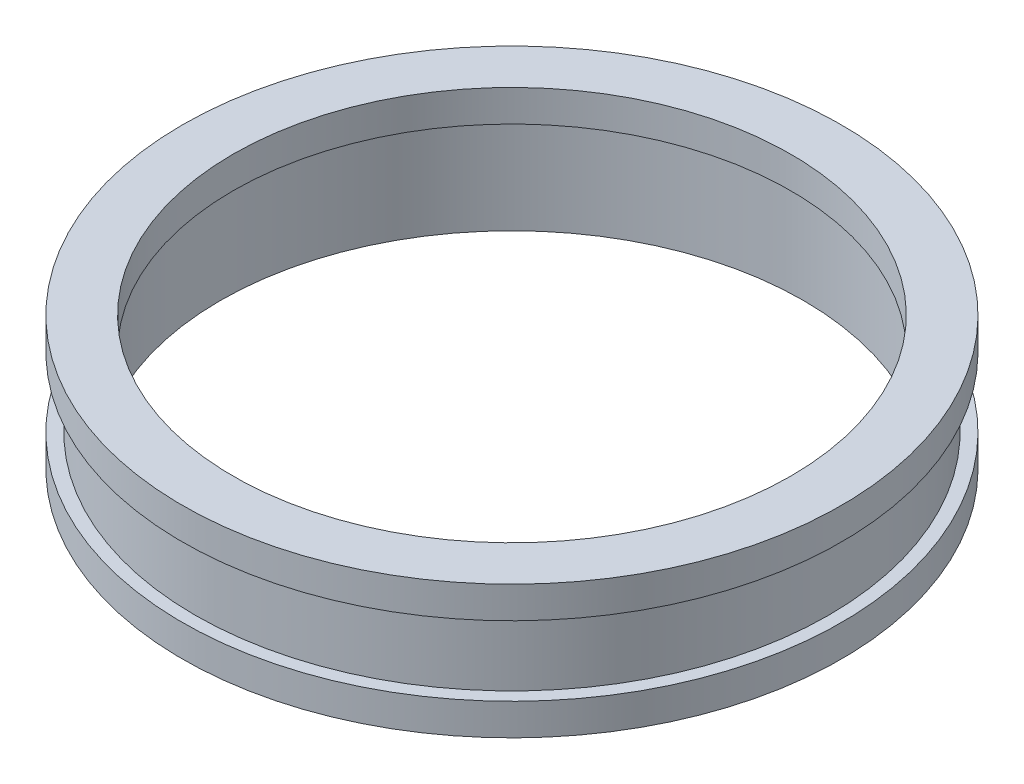
SolidWorks part; units mm, degrees
ref_plane "Front Plane" through (0, 0, 0) normal (0, 0, 1) x (1, 0, 0)
ref_plane "Top Plane" through (0, 0, 0) normal (0, 1, 0) x (1, 0, 0)
ref_plane "Right Plane" through (0, 0, 0) normal (1, 0, 0) x (0, 0, -1)
ref_plane "Plane1" through (0, 0, 0) normal (0, 0, -1) x (-1, 0, 0)
sketch "Sketch1" plane through (0, 0, 0) normal (0, 0, -1) x (-1, 0, 0)
  line L0 (-44, 4.3812) -> (-44, -0.6188)
  line L1 (-44, 4.3812) -> (-52, 4.3812)
  line L2 (-52, 4.3812) -> (-52, -0.6188)
  line L3 (-52, -0.6188) -> (-50, -0.6188)
  line L4 (-50, -0.6188) -> (-50, -11.6188)
  line L5 (-50, -11.6188) -> (-52, -11.6188)
  line L6 (-52, -11.6188) -> (-52, -16.6188)
  line L7 (-52, -16.6188) -> (-46, -16.6188)
  line L8 (-44, -0.6188) -> (-46, -0.6188)
  line L9 (-46, -0.6188) -> (-46, -16.6188)
  line L14 (0, -16.6188) -> (0, 14.3812) construction
  dimension "D1" = 6
  dimension "D2" = 8
  dimension "D3" = 2
  dimension "D4" = 5
revolve "Revolve1" add sketch "Sketch1" angle 360 about L14
